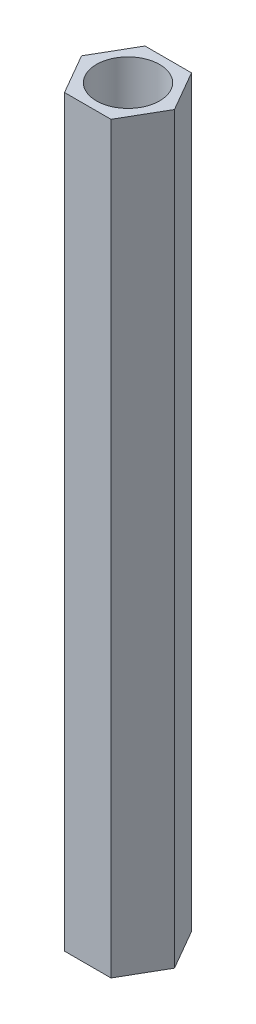
SolidWorks part; units mm, degrees
ref_plane "Front Plane" through (0, 0, 0) normal (0, 0, 1) x (1, 0, 0)
ref_plane "Top Plane" through (0, 0, 0) normal (0, 1, 0) x (1, 0, 0)
ref_plane "Right Plane" through (0, 0, 0) normal (1, 0, 0) x (0, 0, -1)
sketch "Sketch1" plane through (0, 0, 0) normal (0, 1, 0) x (1, 0, 0)
  line L1 (2.5, 0) -> (1.25, 2.1651)
  line L2 (1.25, 2.1651) -> (-1.25, 2.1651)
  line L3 (-1.25, 2.1651) -> (-2.5, 0)
  line L4 (-2.5, 0) -> (-1.25, -2.1651)
  line L5 (-1.25, -2.1651) -> (1.25, -2.1651)
  line L6 (1.25, -2.1651) -> (2.5, 0)
  circle A0 centre (0, 0) radius 2.1651 construction
  dimension "D1" = 2.5
extrude "Boss-Extrude1" add sketch "Sketch1" along normal blind 40
sketch "Sketch30" plane through (0, 40, 0) normal (0, 1, 0) x (1, 0, 0)
  circle A0 centre (0, 0) radius 1.7
extrude "Cut-Extrude1" cut sketch "Sketch30" against normal blind 44 contours A0
